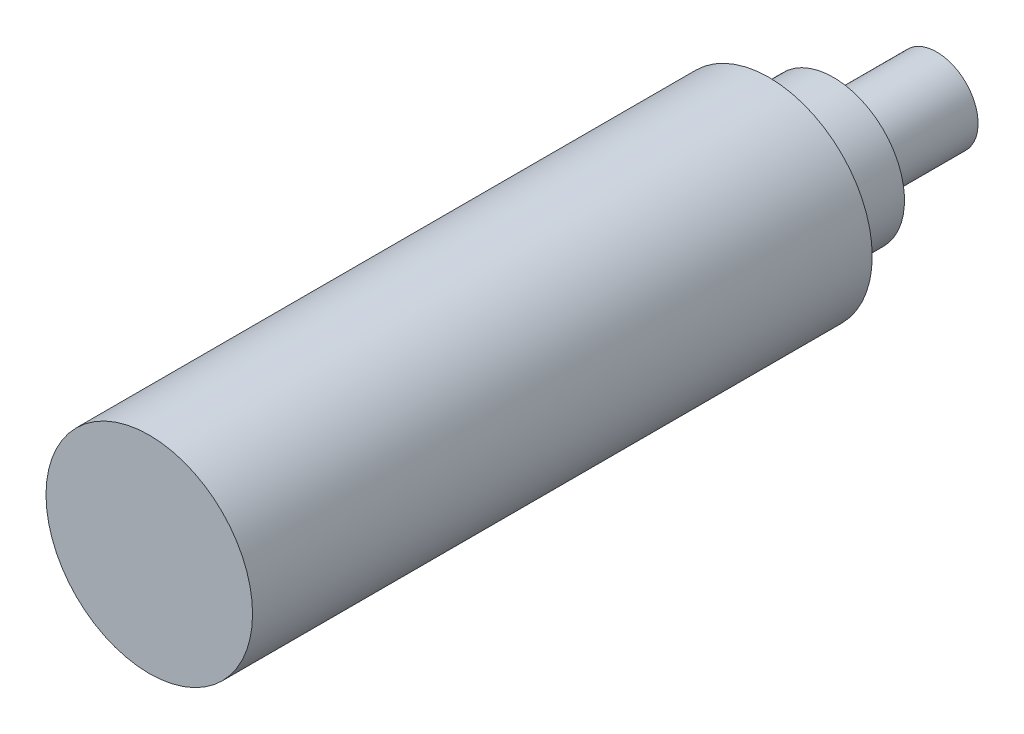
SolidWorks part; units mm, degrees
other "Motor"
ref_plane "Front" through (0, 0, 0) normal (0, 0, 1) x (1, 0, 0)
ref_plane "Top" through (0, 0, 0) normal (0, 1, 0) x (1, 0, 0)
ref_plane "Right" through (0, 0, 0) normal (1, 0, 0) x (0, 0, -1)
sketch "BodySke" plane through (0, 0, 0) normal (0, 0, 1) x (1, 0, 0)
  circle A0 centre (0, 0) radius 4
  dimension "D1" = 8
extrude "Body" add sketch "BodySke" along normal blind 24
sketch "PadSke" plane through (0, 0, 0) normal (0, 0, -1) x (-1, 0, 0)
  circle A0 centre (0, 0) radius 3
  dimension "D1" = 6
extrude "Pad" add sketch "PadSke" along normal blind 0.5
sketch "ThreadSke" plane through (0, 0, -0.5) normal (0, 0, -1) x (-1, 0, 0)
  circle A0 centre (0, 0) radius 2.75
  dimension "D1" = 5.5
extrude "Thread" add sketch "ThreadSke" along normal blind 2
sketch "AxisSke" plane through (0, 0, -2.5) normal (0, 0, -1) x (-1, 0, 0)
  circle A0 centre (0, 0) radius 1.6
  dimension "D1" = 3.2
extrude "Axis" add sketch "AxisSke" along normal blind 4
